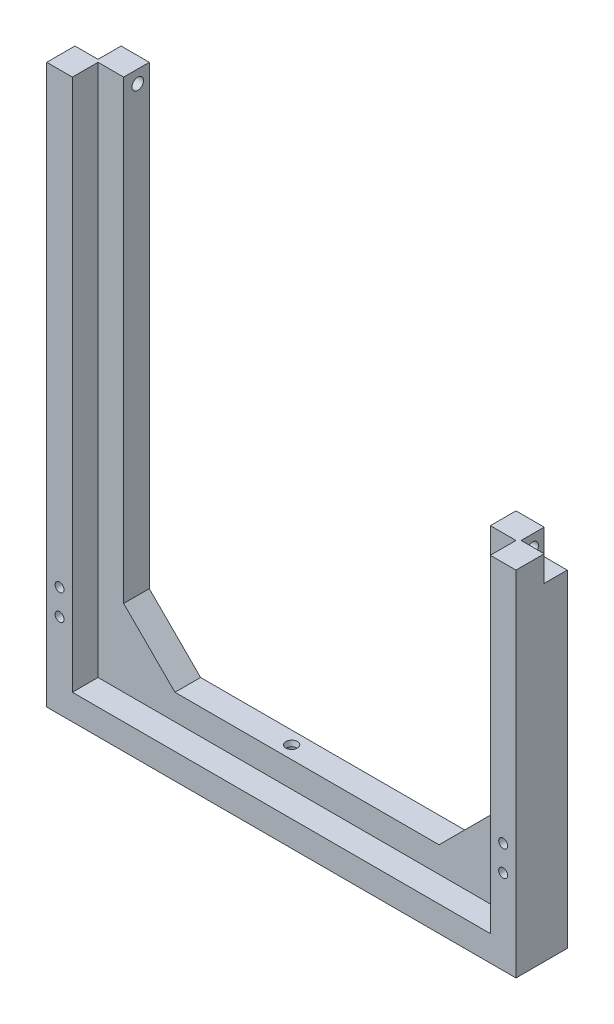
SolidWorks part; units mm, degrees
ref_plane "Front Plane" through (0, 0, 0) normal (0, 0, 1) x (1, 0, 0)
ref_plane "Top Plane" through (0, 0, 0) normal (0, 1, 0) x (1, 0, 0)
ref_plane "Right Plane" through (0, 0, 0) normal (1, 0, 0) x (0, 0, -1)
sketch "Sketch1" plane through (0, 0, 0) normal (0, 0, 1) x (1, 0, 0)
  line L0 (0, 0) -> (-91.5, 0)
  line L1 (-91.5, 0) -> (-91.5, 217.775)
  line L2 (-91.5, 217.775) -> (-71.5, 217.775)
  line L3 (-71.5, 217.775) -> (-71.5, 40)
  line L4 (-51.5, 20) -> (0, 20)
  line L5 (0, 20) -> (0, 0) construction
  line L6 (0, 20) -> (51.5, 20)
  line L7 (71.5, 40) -> (71.5, 137.775)
  line L8 (71.5, 137.775) -> (91.5, 137.775)
  line L9 (91.5, 137.775) -> (91.5, 0)
  line L10 (91.5, 0) -> (0, 0)
  line L11 (-71.5, 40) -> (-51.5, 20)
  line L12 (71.5, 40) -> (51.5, 20)
  dimension "D1" = 217.775
  dimension "D2" = 20
  dimension "D3" = 91.5
  dimension "D4" = 80
  dimension "D5" = 45
  dimension "D6" = 20
  dimension "D7" = 45
  dimension "D8" = 20
extrude "Boss-Extrude1" add sketch "Sketch1" along normal blind 10
sketch "Sketch2" plane through (0, 0, 10) normal (0, 0, 1) x (1, 0, 0)
  line L0 (-81.5, 217.775) -> (-91.5, 217.775)
  line L1 (-71.5, 217.775) -> (-91.5, 217.775) construction
  line L2 (-91.5, 217.775) -> (-91.5, 0)
  line L3 (-91.5, 0) -> (91.5, 0)
  line L4 (91.5, 0) -> (91.5, 137.775)
  line L5 (91.5, 137.775) -> (81.5, 137.775)
  line L6 (91.5, 137.775) -> (71.5, 137.775) construction
  line L7 (81.5, 137.775) -> (81.5, 10)
  line L8 (81.5, 10) -> (-81.5, 10)
  line L9 (-81.5, 10) -> (-81.5, 217.775)
  dimension "D1" = 10
extrude "Boss-Extrude2" add sketch "Sketch2" along normal blind 10
sketch "Sketch3" plane through (0, 217.775, 0) normal (0, 1, 0) x (1, 0, 0)
  line L1 (-91.5, 0) -> (-82.5, 0)
  line L2 (-91.5, 0) -> (-91.5, -9)
  line L3 (-91.5, -9) -> (-82.5, -9)
  line L4 (-82.5, 0) -> (-82.5, -9)
  dimension "D1" = 9
extrude "Cut-Extrude2" cut sketch "Sketch3" against normal blind 10
sketch "Sketch5" plane through (0, 137.775, 0) normal (0, 1, 0) x (1, 0, 0)
  line L1 (91.5, 0) -> (82.5, 0)
  line L2 (91.5, 0) -> (91.5, -9)
  line L3 (91.5, -9) -> (82.5, -9)
  line L4 (82.5, 0) -> (82.5, -9)
  dimension "D1" = 9
extrude "Cut-Extrude3" cut sketch "Sketch5" against normal blind 10
sketch "Sketch6" plane through (-82.5, 0, 0) normal (-1, 0, 0) x (0, 0, 1)
  line L0 (9, 217.775) -> (0, 217.775) construction
  line L1 (0, 207.775) -> (0, 217.775) construction
  circle A0 centre (4.5, 212.775) radius 2.25
  point P4 (4.5, 217.775)
  point P7 (0, 212.775)
  dimension "D1" = 4.5
extrude "Cut-Extrude4" cut sketch "Sketch6" against normal up to surface (11 mm away) up to face at (-71.5, 128.8875, 5)
sketch "Sketch7" plane through (82.5, 0, 0) normal (1, 0, 0) x (0, 0, -1)
  line L0 (0, 137.775) -> (-9, 137.775) construction
  line L1 (0, 127.775) -> (0, 137.775) construction
  circle A0 centre (-4.5, 132.775) radius 2.25
  point P4 (-4.5, 137.775)
  point P7 (0, 132.775)
  dimension "D1" = 4.5
extrude "Cut-Extrude5" cut sketch "Sketch7" against normal up to surface (11 mm away) up to face at (71.5, 88.8875, 5)
sketch "Sketch8" plane through (0, 0, 0) normal (0, 0, -1) x (-1, 0, 0)
  line L0 (91.5, 207.775) -> (91.5, 0) construction
  line L1 (91.5, 0) -> (-91.5, 0) construction
  line L2 (-91.5, 0) -> (-91.5, 127.775) construction
  circle A0 centre (86.5, 33) radius 1.75
  circle A1 centre (-86.5, 33) radius 1.75
  circle A2 centre (-86.5, 43) radius 1.75
  circle A3 centre (86.5, 43) radius 1.75
  dimension "D2" = 3.5
  dimension "D1" = 5
  dimension "D3" = 33
  dimension "D4" = 5
  dimension "D5" = 10
extrude "Cut-Extrude6" cut sketch "Sketch8" against normal through all
sketch "Sketch9" plane through (0, 20, 0) normal (0, 1, 0) x (1, 0, 0)
  line L0 (-51.5, -10) -> (-51.5, 0) construction
  line L1 (-91.5, -20) -> (-91.5, -9) construction
  circle A0 centre (-11, -5) radius 1.75
  point P5 (-51.5, -5)
  dimension "D1" = 3.5
  dimension "D2" = 80.5
extrude "Cut-Extrude7" cut sketch "Sketch9" against normal blind 6
chamfer "Chamfer1" distance 0.5 angle 75 1 edges at (-11, 20, 6.75)
sketch "Sketch10" plane through (0, 0, 0) normal (0, 0, -1) x (-1, 0, 0)
  line L0 (91.5, 0) -> (-91.5, 0) construction
  line L1 (-84.8546, 30.15) -> (-83.2091, 33)
  line L2 (-83.2091, 33) -> (-84.8546, 35.85)
  line L3 (-84.8546, 35.85) -> (-88.1454, 35.85)
  line L4 (-88.1454, 35.85) -> (-89.7909, 33)
  line L5 (-89.7909, 33) -> (-88.1454, 30.15)
  line L6 (-88.1454, 30.15) -> (-84.8546, 30.15)
  line L7 (88.1454, 30.15) -> (89.7909, 33)
  line L8 (89.7909, 33) -> (88.1454, 35.85)
  line L9 (88.1454, 35.85) -> (84.8546, 35.85)
  line L10 (84.8546, 35.85) -> (83.2091, 33)
  line L11 (83.2091, 33) -> (84.8546, 30.15)
  line L12 (84.8546, 30.15) -> (88.1454, 30.15)
  line L14 (-84.8546, 40.15) -> (-83.2091, 43)
  line L15 (-83.2091, 43) -> (-84.8546, 45.85)
  line L16 (-84.8546, 45.85) -> (-88.1454, 45.85)
  line L17 (-88.1454, 45.85) -> (-89.7909, 43)
  line L18 (-89.7909, 43) -> (-88.1454, 40.15)
  line L19 (-88.1454, 40.15) -> (-84.8546, 40.15)
  line L20 (88.1454, 40.15) -> (89.7909, 43)
  line L21 (89.7909, 43) -> (88.1454, 45.85)
  line L22 (88.1454, 45.85) -> (84.8546, 45.85)
  line L23 (84.8546, 45.85) -> (83.2091, 43)
  line L24 (83.2091, 43) -> (84.8546, 40.15)
  line L25 (84.8546, 40.15) -> (88.1454, 40.15)
  circle A0 centre (-86.5, 33) radius 2.85 construction
  circle A1 centre (86.5, 33) radius 2.85 construction
  circle A2 centre (-86.5, 43) radius 2.85 construction
  circle A3 centre (86.5, 43) radius 2.85 construction
  circle A4 centre (-86.5, 43) radius 1.75 construction
  circle A5 centre (-86.5, 43) radius 1.75 construction
  circle A6 centre (86.5, 43) radius 1.75 construction
  circle A7 centre (86.5, 43) radius 1.75 construction
  dimension "D1" = 5.7
extrude "Cut-Extrude8" cut sketch "Sketch10" against normal blind 2.1
